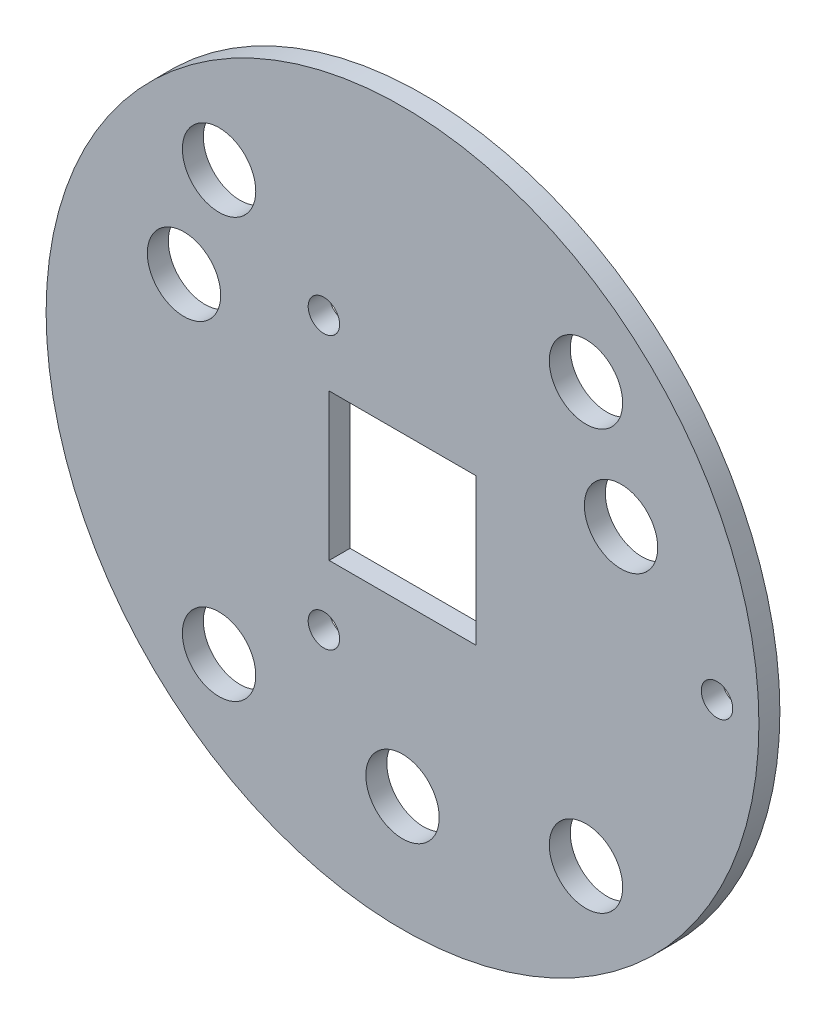
SolidWorks part; units mm, degrees
ref_plane "Front Plane" through (0, 0, 0) normal (0, 0, 1) x (1, 0, 0)
ref_plane "Top Plane" through (0, 0, 0) normal (0, 1, 0) x (1, 0, 0)
ref_plane "Right Plane" through (0, 0, 0) normal (1, 0, 0) x (0, 0, -1)
sketch "Sketch1" plane through (0, 0, 0) normal (0, 0, 1) x (1, 0, 0)
  line L0 (0, 0) -> (34, 0) construction
  line L1 (-7, 7) -> (7, 7)
  line L2 (-7, 7) -> (-7, -7)
  line L3 (-7, -7) -> (7, -7)
  line L4 (7, 7) -> (7, -7)
  line L5 (0, 0) -> (0, -23) construction
  line L6 (0, 0) -> (-34, 0) construction
  line L7 (0, 0) -> (-20.8451, 9.7202) construction
  line L8 (0, 0) -> (20.8451, 9.7202) construction
  circle A0 centre (0, 0) radius 34
  circle A1 centre (15, 0) radius 1.5 construction
  circle A2 centre (30, 0) radius 1.5
  circle A3 centre (-7.5, -12.9904) radius 1.5
  circle A4 centre (-15, -25.9808) radius 1.5 construction
  circle A5 centre (-7.5, 12.9904) radius 1.5
  circle A6 centre (-15, 25.9808) radius 1.5 construction
  circle A7 centre (-17.5, 20) radius 3.5
  circle A8 centre (17.5, 20) radius 3.5
  circle A9 centre (-17.5, -20) radius 3.5
  circle A10 centre (17.5, -20) radius 3.5
  circle A11 centre (20.8451, 9.7202) radius 3.5
  circle A12 centre (0, -23) radius 3.5
  circle A13 centre (-20.8451, 9.7202) radius 3.5
  circle A14 centre (0, 0) radius 23 construction
  point P23 (0, 0)
  dimension "D1" = 68
  dimension "D3" = 3
  dimension "D9" = 7
  dimension "D11" = 7
  dimension "D12" = 46
  dimension "D2" = 14
  dimension "D4" = 15
  dimension "D5" = 15
  dimension "D7" = 115
  dimension "D8" = 20
  dimension "D10" = 115
  dimension "D13" = 90
  dimension "D14" = 17.5
  dimension "D6" = 3
extrude "Boss-Extrude1" add sketch "Sketch1" along normal blind 2
